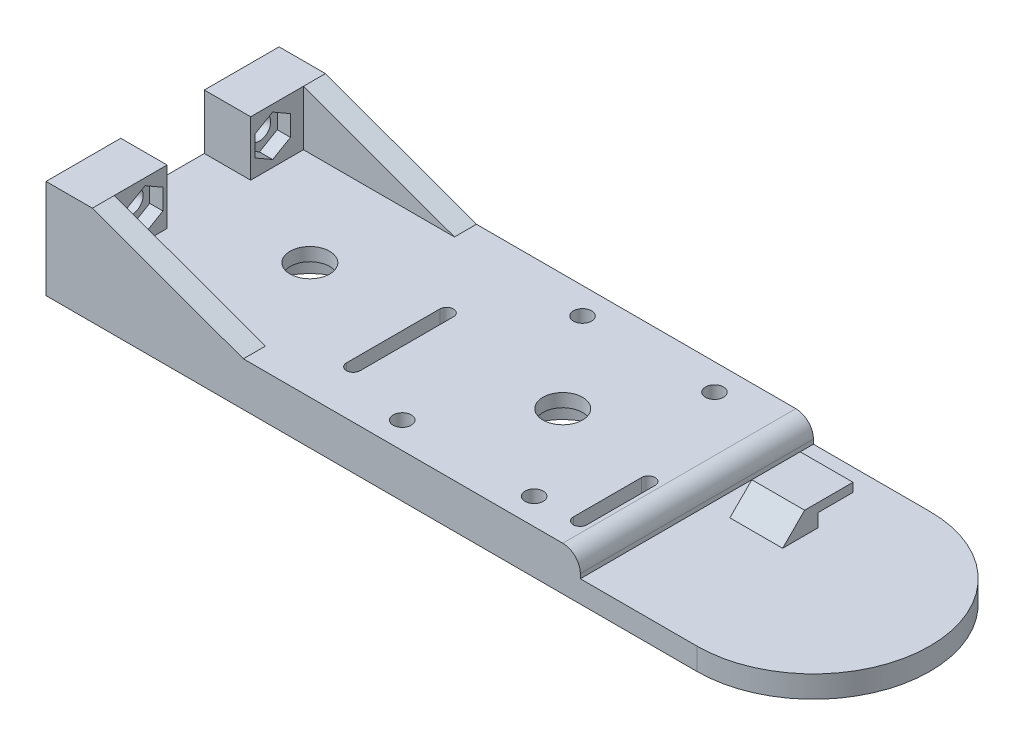
SolidWorks part; units mm, degrees
ref_plane "Front Plane" through (0, 0, 0) normal (0, 0, 1) x (1, 0, 0)
ref_plane "Top Plane" through (0, 0, 0) normal (0, 1, 0) x (1, 0, 0)
ref_plane "Right Plane" through (0, 0, 0) normal (1, 0, 0) x (0, 0, -1)
sketch "Sketch1" plane through (0, 0, 0) normal (0, 1, 0) x (1, 0, 0)
  line L1 (-74, 26.5) -> (74, 26.5)
  line L2 (-74, 26.5) -> (-74, -26.5)
  line L3 (-74, -26.5) -> (74, -26.5)
  arc A0 (74, -26.5) -> (74, 26.5) centre (74, 0) ccw
  point P0 (0, 0)
  dimension "D1" = 148
  dimension "D2" = 53
extrude "Boss-Extrude1" add sketch "Sketch1" along normal blind 10
sketch "Sketch2" plane through (0, 10, 0) normal (0, 1, 0) x (1, 0, 0)
  line L0 (-74, 26.5) -> (-74, -26.5) construction
  line L1 (-74, -26.5) -> (74, -26.5) construction
  line L2 (-74, -9.5) -> (-63.4636, -9.5)
  line L3 (-74, -9.5) -> (-74, -26.5)
  line L4 (-74, -26.5) -> (-63.4636, -26.5)
  line L5 (-63.4636, -9.5) -> (-63.4636, -26.5)
  dimension "D1" = 17
extrude "Boss-Extrude2" add sketch "Sketch2" along normal blind 12.5
sketch "Sketch3" plane through (0, 0, 26.5) normal (0, 0, 1) x (1, 0, 0)
  line L0 (-63.4636, 22.5) -> (-29.1201, 10)
  line L1 (-63.4636, 10) -> (74, 10) construction
  dimension "D1" = 20
rib "Rib1" sketch "Sketch3" sketch "Sketch3" thickness 5 extrusion direction parallel to sketch draft on no parameters "D1"=5
sketch "Sketch4" plane through (-63.4636, 0, 0) normal (1, 0, 0) x (0, 0, -1)
  line L0 (-21.5, 10) -> (-21.5, 22.5) construction
  circle A0 centre (-14.5, 16.25) radius 2.55
  dimension "D1" = 5.1
  dimension "D2" = 7
extrude "Cut-Extrude1" cut sketch "Sketch4" against normal up to next
sketch "Sketch5" plane through (-63.4636, 0, 0) normal (1, 0, 0) x (0, 0, -1)
  line L0 (-21.5, 22.5) -> (-21.5, 10) construction
  line L1 (-10.45, 13.9117) -> (-10.45, 18.5883)
  line L2 (-10.45, 18.5883) -> (-14.5, 20.9265)
  line L3 (-14.5, 20.9265) -> (-18.55, 18.5883)
  line L4 (-18.55, 18.5883) -> (-18.55, 13.9117)
  line L5 (-18.55, 13.9117) -> (-14.5, 11.5735)
  line L6 (-14.5, 11.5735) -> (-10.45, 13.9117)
  circle A0 centre (-14.5, 16.25) radius 4.05 construction
  dimension "D1" = 8.1
extrude "Cut-Extrude2" cut sketch "Sketch5" against normal blind 3
mirror "Mirror1" about plane through (0, 0, 0) normal (0, 0, 1) of "Cut-Extrude2", "Cut-Extrude1", "Rib1", "Boss-Extrude2"
sketch "Sketch6" plane through (0, 0, 0) normal (0, -1, 0) x (1, 0, 0)
  circle A0 centre (-40.5, 0) radius 11.1
  dimension "D1" = 22.2
  dimension "D2" = 40.5
extrude "Cut-Extrude3" cut sketch "Sketch6" against normal blind 7
sketch "Sketch8" plane through (0, 7, 0) normal (0, -1, 0) x (1, 0, 0)
  circle A0 centre (-40.5, 0) radius 4.5
  dimension "D1" = 9
extrude "Cut-Extrude5" cut sketch "Sketch8" against normal up to next
sketch "Sketch9" plane through (0, 0, 0) normal (0, -1, 0) x (1, 0, 0)
  circle A0 centre (17, 0) radius 11.1
  dimension "D1" = 22.2
  dimension "D2" = 17
extrude "Cut-Extrude6" cut sketch "Sketch9" against normal blind 7
sketch "Sketch10" plane through (0, 7, 0) normal (0, -1, 0) x (1, 0, 0)
  circle A0 centre (17, 0) radius 4.5
  dimension "D1" = 9
extrude "Cut-Extrude7" cut sketch "Sketch10" against normal up to next
sketch "Sketch12" plane through (0, 10, 0) normal (0, 1, 0) x (1, 0, 0)
  line L0 (1, 20.5) -> (31, 20.5) construction
  line L1 (74, 26.5) -> (-29.1201, 26.5) construction
  line L2 (-74, 9.5) -> (-74, -9.5) construction
  circle A0 centre (1, 20.5) radius 2.05
  circle A1 centre (31, 20.5) radius 2.05
  dimension "D4" = 4.1
  dimension "D5" = 4.1
  dimension "D1" = 30
  dimension "D2" = 6
  dimension "D3" = 75
extrude "Cut-Extrude9" cut sketch "Sketch12" against normal through all
sketch "Sketch13" plane through (0, 0, 0) normal (0, -1, 0) x (1, 0, 0)
  line L1 (4.6477, -22.6114) -> (4.6523, -18.3967)
  line L2 (4.6523, -18.3967) -> (1.0047, -16.2853)
  line L3 (1.0047, -16.2853) -> (-2.6477, -18.3886)
  line L4 (-2.6477, -18.3886) -> (-2.6523, -22.6033)
  line L5 (-2.6523, -22.6033) -> (0.9953, -24.7147)
  line L6 (0.9953, -24.7147) -> (4.6477, -22.6114)
  line L7 (34.5579, -22.7593) -> (34.7356, -18.5484)
  line L8 (34.7356, -18.5484) -> (31.1776, -16.2891)
  line L9 (31.1776, -16.2891) -> (27.4421, -18.2407)
  line L10 (27.4421, -18.2407) -> (27.2644, -22.4516)
  line L11 (27.2644, -22.4516) -> (30.8224, -24.7109)
  line L12 (30.8224, -24.7109) -> (34.5579, -22.7593)
  circle A0 centre (1, -20.5) radius 3.65 construction
  circle A1 centre (31, -20.5) radius 3.65 construction
  dimension "D1" = 7.3
  dimension "D2" = 7.3
extrude "Cut-Extrude10" cut sketch "Sketch13" against normal blind 3
mirror "Mirror2" about plane through (0, 0, 0) normal (0, 0, 1) of "Cut-Extrude9", "Cut-Extrude10"
sketch "Sketch14" plane through (0, 0, 0) normal (0, -1, 0) x (1, 0, 0)
  line L0 (-15.0576, 15.5692) -> (-15.0576, -5.6615) construction
  line L1 (-13.5076, 15.5692) -> (-13.5076, -5.6615)
  line L2 (-16.6076, 15.5692) -> (-16.6076, -5.6615)
  arc A0 (-13.5076, 15.5692) -> (-16.6076, 15.5692) centre (-15.0576, 15.5692) ccw
  arc A1 (-16.6076, -5.6615) -> (-13.5076, -5.6615) centre (-15.0576, -5.6615) ccw
  point P2 (-15.0576, 4.9538)
extrude "Cut-Extrude11" cut sketch "Sketch14" against normal up to next
sketch "Sketch15" plane through (0, 0, 0) normal (0, -1, 0) x (1, 0, 0)
  line L0 (41.0717, 20.1247) -> (41.0717, 4.6169) construction
  line L3 (42.6217, 20.1247) -> (42.6217, 4.6169)
  line L4 (39.5217, 20.1247) -> (39.5217, 4.6169)
  arc A2 (42.6217, 20.1247) -> (39.5217, 20.1247) centre (41.0717, 20.1247) ccw
  arc A3 (39.5217, 4.6169) -> (42.6217, 4.6169) centre (41.0717, 4.6169) ccw
  point P2 (41.0717, 12.3708)
extrude "Cut-Extrude12" cut sketch "Sketch15" against normal up to next
sketch "Sketch16" plane through (0, 10, 0) normal (0, 1, 0) x (1, 0, 0)
  line L1 (47.5, 46.9915) -> (100.5, 46.9915)
  line L2 (47.5, 46.9915) -> (47.5, -46.9915)
  line L3 (47.5, -46.9915) -> (100.5, -46.9915)
  line L4 (100.5, 46.9915) -> (100.5, -46.9915)
  line L5 (47.5, 46.9915) -> (100.5, -46.9915) construction
  line L6 (47.5, -46.9915) -> (100.5, 46.9915) construction
  point P0 (74, 0)
extrude "Cut-Extrude13" cut sketch "Sketch16" against normal blind 5
fillet "Fillet3" radius 4 1 edges at (47.5, 10, 0)
sketch "Sketch17" plane through (0, 5, 0) normal (0, 1, 0) x (1, 0, 0)
  line L0 (47.5, 26.5) -> (47.5, -26.5) construction
  line L1 (52.5, 10.5) -> (64.5, 10.5)
  line L2 (52.5, 10.5) -> (52.5, 7.5)
  line L3 (52.5, 7.5) -> (64.5, 7.5)
  line L4 (64.5, 10.5) -> (64.5, 7.5)
  line L5 (74, 26.5) -> (47.5, 26.5) construction
  dimension "D1" = 3
  dimension "D2" = 12
  dimension "D3" = 5
  dimension "D4" = 16
extrude "Boss-Extrude3" add sketch "Sketch17" along normal blind 5
sketch "Sketch18" plane through (0, 0, -10.5) normal (0, 0, -1) x (-1, 0, 0)
  line L0 (-52.5, 10) -> (-52.5, 5) construction
  line L1 (-52.5, 8) -> (-64.5, 8)
  line L2 (-52.5, 8) -> (-52.5, 10)
  line L3 (-52.5, 10) -> (-64.5, 10)
  line L4 (-64.5, 8) -> (-64.5, 10)
  dimension "D1" = 2
extrude "Boss-Extrude4" add sketch "Sketch18" along normal blind 8
sketch "Sketch19" plane through (64.5, 0, 0) normal (1, 0, 0) x (0, 0, -1)
  line L0 (7.5, 10) -> (2.5, 5)
  line L1 (26.5, 5) -> (-26.5, 5) construction
  dimension "D1" = 45
rib "Rib2" sketch "Sketch19" sketch "Sketch19" thickness 12 extrusion direction parallel to sketch draft on no parameters "D1"=12
